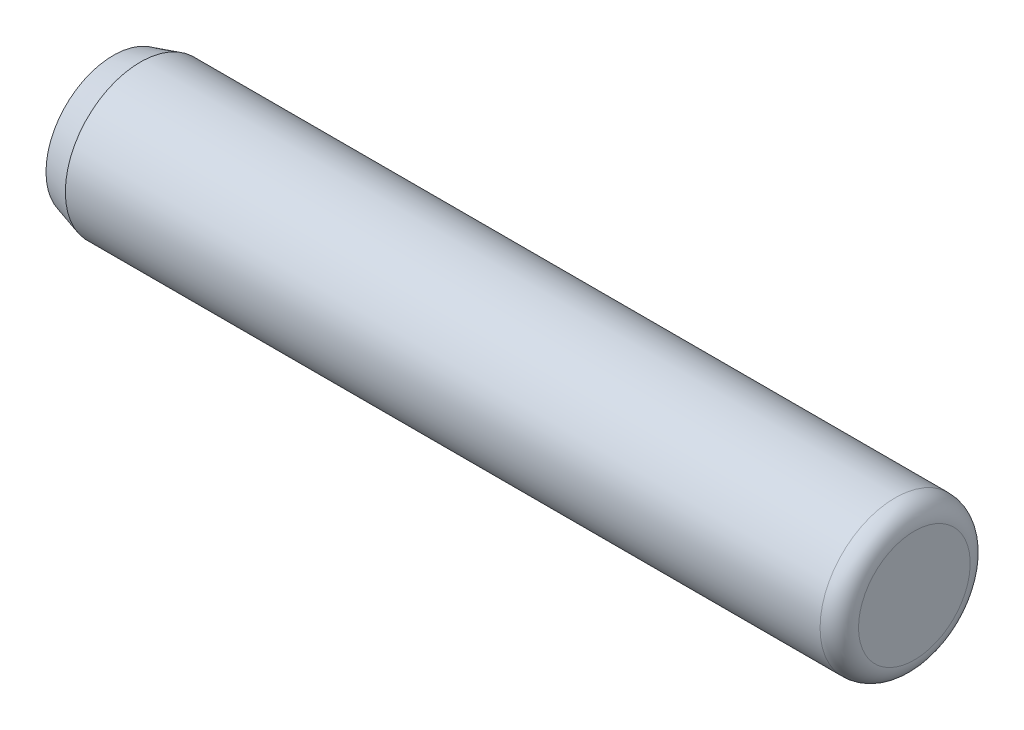
SolidWorks part; units mm, degrees
material "AISI 304"
ref_plane "Front" through (0, 0, 0) normal (0, 0, 1) x (1, 0, 0)
ref_plane "Top" through (0, 0, 0) normal (0, 1, 0) x (1, 0, 0)
ref_plane "Right" through (0, 0, 0) normal (1, 0, 0) x (0, 0, -1)
sketch "Sketch1" plane through (0, 0, 0) normal (1, 0, 0) x (0, 0, -1)
  circle A0 centre (0, 0) radius 1.19 construction
  point P3 (0, 1.19)
  dimension "Diameter" = 2.38
sketch "Sketch2" plane through (0, 0, 0) normal (0, 0, 1) x (1, 0, 0)
  line L0 (-6.35, 0) -> (6.35, 0) construction
  line L1 (6.35, 0.8852) -> (6.35, -0.6481) construction
  line L2 (-6.35, 1.0668) -> (-6.35, -1.0668) construction
  line L3 (-6.35, 1.0668) -> (-6.35, 1.19) construction
  line L4 (-6.35, -1.0668) -> (-6.35, -1.19) construction
  line L5 (-6.35, 1.0668) -> (-5.9204, 1.19) construction
  line L6 (-5.9204, 1.19) -> (6.0452, 1.19) construction
  arc A0 (6.0452, 1.19) -> (6.35, 0.8852) centre (6.0452, 0.8852) cw construction
  point P6 (-3.97, 0)
  point P8 (3.97, 0)
  point P23 (5.5626, 1.19)
  dimension "Crown Radius" = 0.3048
  dimension "Length" = 12.7
  dimension "D1" = 2.38
  dimension "D2" = 2.38
  dimension "Point Diameter" = 2.1336
  dimension "D3" = 16
  dimension "Crown Height" = 0.7874
sketch "Sketch3" plane through (0, 0, 0) normal (0, 0, 1) x (1, 0, 0)
  line L0 (6.35, 0.8852) -> (6.35, -0.6481) construction
  line L1 (-5.9204, 1.19) -> (6.0452, 1.19) construction
  line L2 (-6.35, 1.0668) -> (-5.9204, 1.19) construction
  line L3 (-6.35, 1.0668) -> (-6.35, -1.0668) construction
  line L4 (-6.35, 0) -> (6.35, 0) construction
  line L5 (6.35, 0.8852) -> (6.35, 0)
  line L6 (-5.9204, 1.19) -> (6.0452, 1.19)
  line L7 (-6.35, 1.0668) -> (-5.9204, 1.19)
  line L8 (-6.35, 1.0668) -> (-6.35, 0)
  line L9 (-6.35, 0) -> (6.35, 0)
  arc A0 (6.35, 0.8852) -> (6.0452, 1.19) centre (6.0452, 0.8852) ccw construction
  arc A1 (6.35, 0.8852) -> (6.0452, 1.19) centre (6.0452, 0.8852) ccw
revolve "Revolve1" add sketch "Sketch3" angle 360 about L0
equation "\"D1@Sketch2\" = \"Diameter@Sketch1\""
equation "\"D2@Sketch2\" = \"Diameter@Sketch1\""
